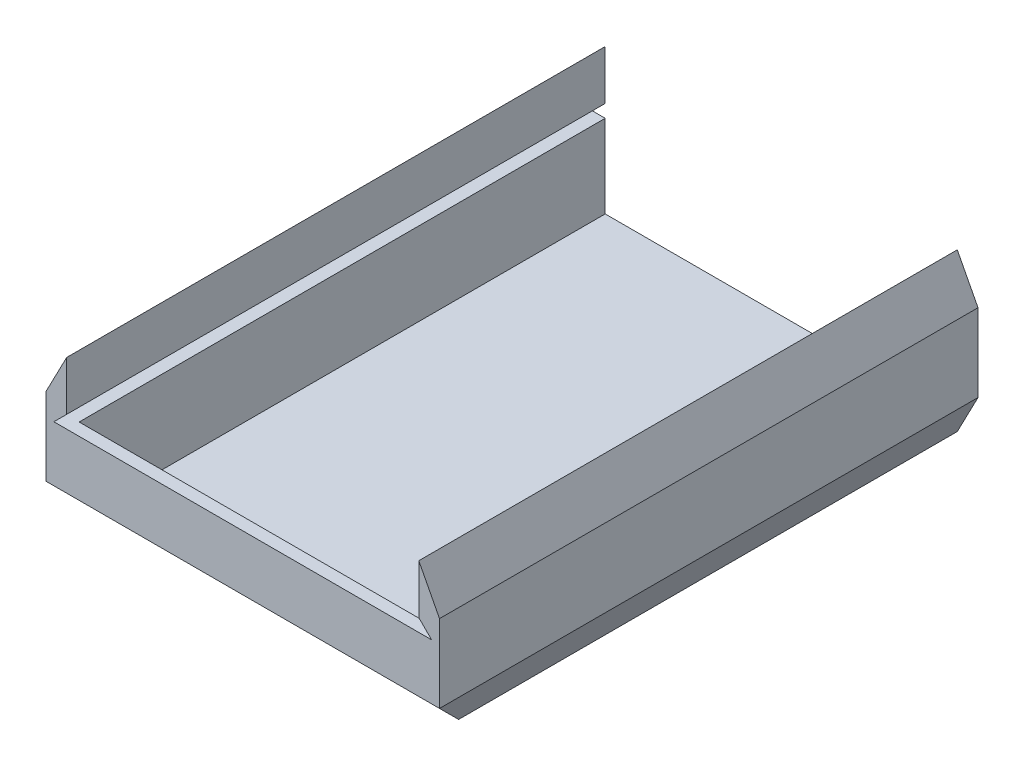
SolidWorks part; units mm, degrees
ref_plane "Front Plane" through (0, 0, 0) normal (0, 0, 1) x (1, 0, 0)
ref_plane "Top Plane" through (0, 0, 0) normal (0, 1, 0) x (1, 0, 0)
ref_plane "Right Plane" through (0, 0, 0) normal (1, 0, 0) x (0, 0, -1)
sketch "Sketch1" plane through (0, 0, 0) normal (0, 1, 0) x (1, 0, 0)
  line L1 (0, 0) -> (85, 0)
  line L2 (0, 0) -> (0, 130)
  line L3 (0, 130) -> (85, 130)
  line L4 (85, 0) -> (85, 130)
  dimension "D1" = 85
  dimension "D2" = 130
extrude "Boss-Extrude1 (Base)" add sketch "Sketch1" along normal blind 3
sketch "Sketch4" plane through (0, 0, 0) normal (0, 0, 1) x (1, 0, 0)
  line L0 (-3.1, 23) -> (0, 26.1)
  line L1 (0, 26.1) -> (0, 23)
  line L2 (0, 23) -> (-3.1, 23)
  line L3 (0, 3) -> (85, 3) construction
  line L6 (0, 3) -> (0, 0) construction
  line L7 (42.5, 28.9013) -> (42.5, -8.4397) construction
  line L8 (85, 3) -> (85, 0) construction
  line L9 (85, 23) -> (88.1, 23)
  line L10 (85, 26.1) -> (85, 23)
  line L11 (88.1, 23) -> (85, 26.1)
  dimension "D1" = 20
  dimension "D2" = 3.1
  dimension "D3" = 3.1
  dimension "D4" = 42.5
sketch "Sketch5" plane through (0, 0, 0) normal (0, 0, 1) x (1, 0, 0)
  line L11 (-5, 28.3909) -> (0, 38)
  line L12 (0, 38) -> (0, 0)
  line L13 (0, 0) -> (-5, 9.6091)
  line L14 (-5, 9.6091) -> (-5, 28.3909)
  line L16 (0, 3) -> (85, 3) construction
  line L21 (42.5, 26.5229) -> (42.5, 7.7495) construction
  line L22 (85, 3) -> (85, 0) construction
  line L23 (90, 9.6091) -> (90, 28.3909)
  line L24 (85, 0) -> (90, 9.6091)
  line L25 (85, 38) -> (85, 0)
  line L26 (90, 28.3909) -> (85, 38)
  dimension "D1" = 5
  dimension "D2" = 35
  dimension "D3" = 42.5
extrude "Boss-Extrude4 (Side Walls)" add sketch "Sketch5" against normal through all
extrude "Cut-Extrude2 (Guide Holes)" cut sketch "Sketch4" against normal through all
sketch "Sketch15" plane through (0, 0, 0) normal (0, 0, 1) x (1, 0, 0)
  line L1 (0, 23) -> (85, 23)
  line L2 (0, 23) -> (0, 3)
  line L3 (0, 3) -> (85, 3)
  line L4 (85, 23) -> (85, 3)
  line L6 (85, 23) -> (85, 3) construction
extrude "Boss-Extrude9 (Front Wall)" add sketch "Sketch15" against normal blind 3
chamfer "Chamfer5 (Front Chamfer)" distance 9.61 angle 45 1 edges at (42.5, 0, 0)
chamfer "Chamfer6 (Front Chamfer Cleanup)" distance 5 angle 45 1 edges at (42.5, 3, -3)
